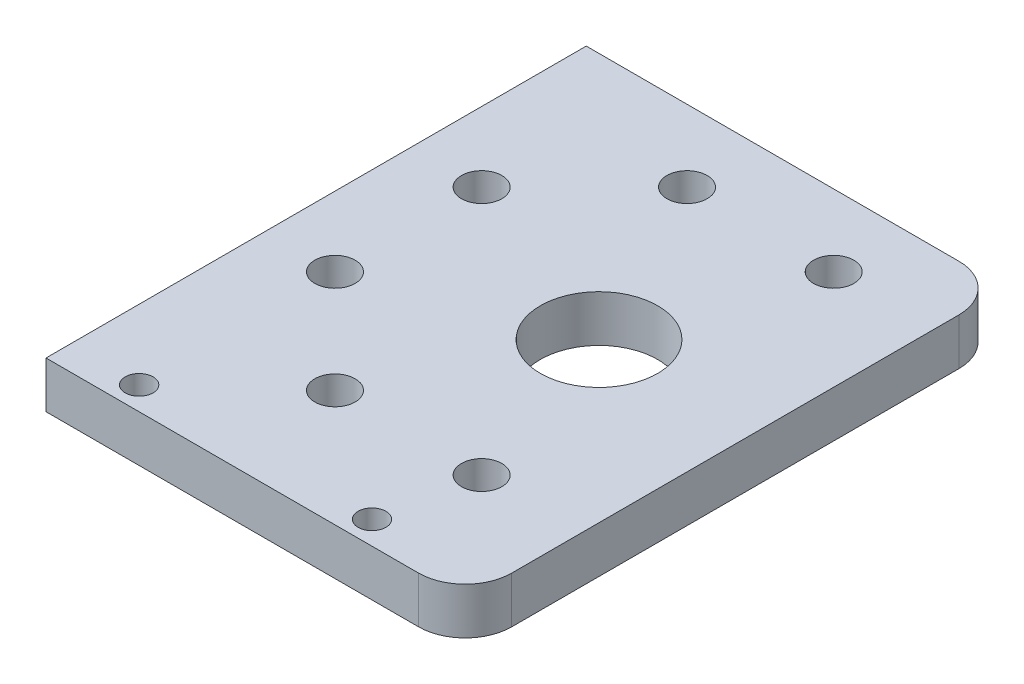
SolidWorks part; units mm, degrees
ref_plane "Front Plane" through (0, 0, 0) normal (0, 0, 1) x (1, 0, 0)
ref_plane "Top Plane" through (0, 0, 0) normal (0, 1, 0) x (1, 0, 0)
ref_plane "Right Plane" through (0, 0, 0) normal (1, 0, 0) x (0, 0, -1)
sketch "Sketch1" plane through (0, 0, 0) normal (0, 1, 0) x (1, 0, 0)
  line L1 (-28.575, 36.83) -> (28.575, 36.83)
  line L2 (-28.575, 36.83) -> (-28.575, -36.83)
  line L3 (-28.575, -36.83) -> (28.575, -36.83)
  line L4 (28.575, 36.83) -> (28.575, -36.83)
  line L5 (-28.575, 36.83) -> (28.575, -36.83) construction
  line L6 (-28.575, -36.83) -> (28.575, 36.83) construction
  point P0 (0, 0)
  dimension "D1" = 73.66
  dimension "D2" = 57.15
extrude "Boss-Extrude1" add sketch "Sketch1" along normal blind 6.35 contours L1 L4 L3 L2
hole_wizard "#6 Clearance Hole1" positions "Sketch2" profile "Sketch3" hole size "#6" standard "ANSI Inch"
sketch "Sketch2" plane through (0, 6.35, 0) normal (0, 1, 0) x (1, 0, 0)
  line L0 (-28.575, -36.83) -> (28.575, -36.83) construction
  line L1 (-28.575, 36.83) -> (-28.575, -36.83) construction
  point P0 (-19.05, -33.655)
  point P2 (12.7, -33.655)
  point P7 (0, 0)
  dimension "D1" = 31.75
  dimension "D2" = 3.175
  dimension "D3" = 9.525
sketch "Sketch3" plane through (-19.05, 6.35, 33.655) normal (1, 0, 0) x (0, 0, 1)
  line L0 (0, 0) -> (0, 13.8408)
  line L1 (0, 13.8408) -> (1.8986, 12.7)
  line L2 (1.8986, 12.7) -> (1.8986, 0)
  line L5 (1.8986, 0) -> (0, 0)
  line L10 (0, 13.8408) -> (-1.8987, 12.7) construction
  line L11 (0, -6.35) -> (0, 107.95) construction
  dimension "Hole Dia." = 3.7973
  dimension "Hole Depth" = 12.7
  dimension "Drill Angle" = 118
hole_wizard "M5 Clearance Hole1" positions "Sketch4" profile "Sketch5" hole size "M5" standard "ANSI Metric"
sketch "Sketch4" plane through (0, 6.35, 0) normal (0, 1, 0) x (1, 0, 0)
  line L1 (-19.05, -6.955) -> (-19.05, 13.045) construction
  line L3 (-28.575, 36.83) -> (-28.575, -36.83) construction
  line L4 (-28.575, -36.83) -> (28.575, -36.83) construction
  point P0 (-19.05, 13.045)
  point P3 (-19.05, -6.955)
  point P16 (6.95, 3.045)
  point P20 (14.95, 27.045)
  point P22 (14.95, -20.955)
  point P26 (-5.05, 27.045)
  point P28 (-5.05, -20.955)
  point P40 (-19.05, 3.045)
  point P41 (-3.7316, 6.7418)
  point P42 (0, 3.2412)
  dimension "D1" = 9.525
  dimension "D2" = 20
  dimension "D3" = 15.875
  dimension "D4" = 26
  dimension "D5" = 8
  dimension "D6" = 24
  dimension "D7" = 48
  dimension "D8" = 20
sketch "Sketch5" plane through (-19.05, 6.35, -13.045) normal (1, 0, 0) x (0, 0, 1)
  line L0 (0, 0) -> (0, 14.3524)
  line L1 (0, 14.3524) -> (2.75, 12.7)
  line L2 (2.75, 12.7) -> (2.75, 0)
  line L5 (2.75, 0) -> (0, 0)
  line L10 (0, 14.3524) -> (-2.75, 12.7) construction
  line L11 (0, -6.35) -> (0, 107.95) construction
  dimension "Hole Dia." = 5.5
  dimension "Hole Depth" = 12.7
  dimension "Drill Angle" = 118
sketch "Sketch6" plane through (0, 6.35, 0) normal (0, 1, 0) x (1, 0, 0)
  circle A0 centre (6.95, 3.045) radius 8
  dimension "D1" = 16
extrude "Cut-Extrude1" cut sketch "Sketch6" against normal blind 6.35
hole_wizard "Tap Drill for #6-32 Tap1" positions "Sketch7" profile "Sketch8" hole size "#6-32" standard "ANSI Inch"
sketch "Sketch7" plane through (-28.575, 0, 0) normal (-1, 0, 0) x (0, 0, 1)
  line L0 (-36.83, 6.35) -> (-36.83, 0) construction
  line L1 (36.83, 6.35) -> (36.83, 0) construction
  line L3 (-36.83, 6.35) -> (36.83, 6.35) construction
  point P0 (26.67, 3.175)
  point P2 (-21.59, 3.175)
  point P14 (27.5187, 6.35)
  point P19 (0, 0)
  dimension "D1" = 15.24
  dimension "D2" = 10.16
  dimension "D3" = 3.175
sketch "Sketch8" plane through (-28.575, 3.175, 26.67) normal (0, 1, 0) x (0, 0, 1)
  line L0 (0, 0) -> (0, 13.5127)
  line L1 (0, 13.5127) -> (1.3525, 12.7)
  line L2 (1.3525, 12.7) -> (1.3525, 0)
  line L5 (1.3525, 0) -> (0, 0)
  line L10 (0, 13.5127) -> (-1.3526, 12.7) construction
  line L11 (0, -6.35) -> (0, 107.95) construction
  dimension "Hole Dia." = 2.7051
  dimension "Hole Depth" = 12.7
  dimension "Drill Angle" = 118
fillet "Fillet1" radius 6.35 2 edges at (28.575, 3.175, -36.83) (28.575, 3.175, 36.83)
